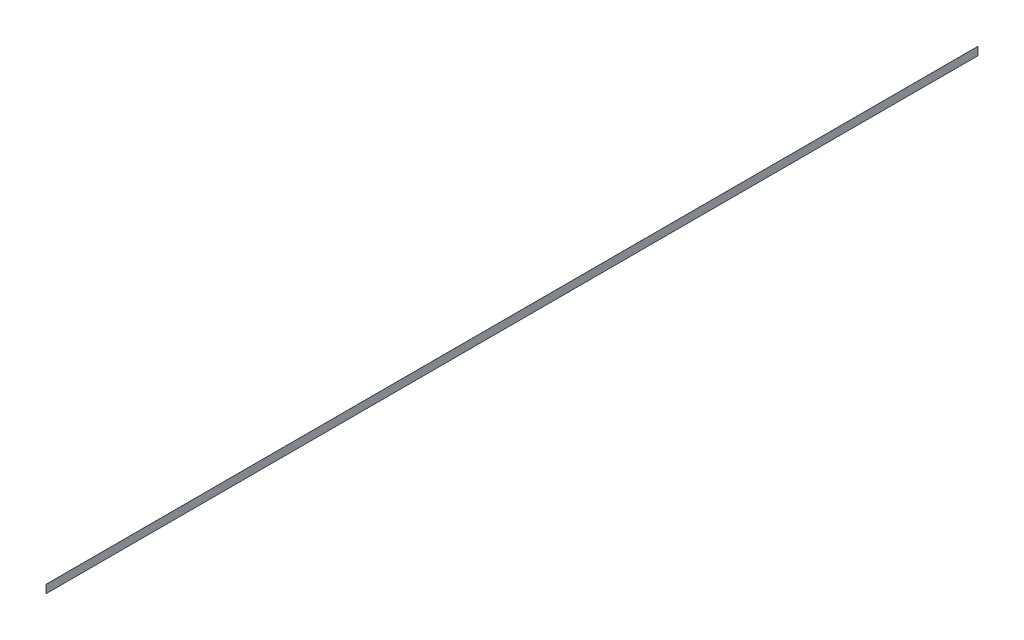
SolidWorks part; units mm, degrees
ref_plane "Front Plane" through (0, 0, 0) normal (0, 0, 1) x (1, 0, 0)
ref_plane "Top Plane" through (0, 0, 0) normal (0, 1, 0) x (1, 0, 0)
ref_plane "Right Plane" through (0, 0, 0) normal (1, 0, 0) x (0, 0, -1)
sketch "Sketch1" plane through (0, 0, 0) normal (0, 0, 1) x (1, 0, 0)
  line L1 (-0.1, -17.5) -> (0.1, -17.5)
  line L2 (-0.1, -17.5) -> (-0.1, 17.5)
  line L3 (-0.1, 17.5) -> (0.1, 17.5)
  line L4 (0.1, -17.5) -> (0.1, 17.5)
  line L5 (-0.1, -17.5) -> (0.1, 17.5) construction
  line L6 (-0.1, 17.5) -> (0.1, -17.5) construction
  point P0 (0, 0)
  dimension "D1" = 35
  dimension "D2" = 0.2
extrude "Boss-Extrude1" add sketch "Sketch1" along normal blind 4000
